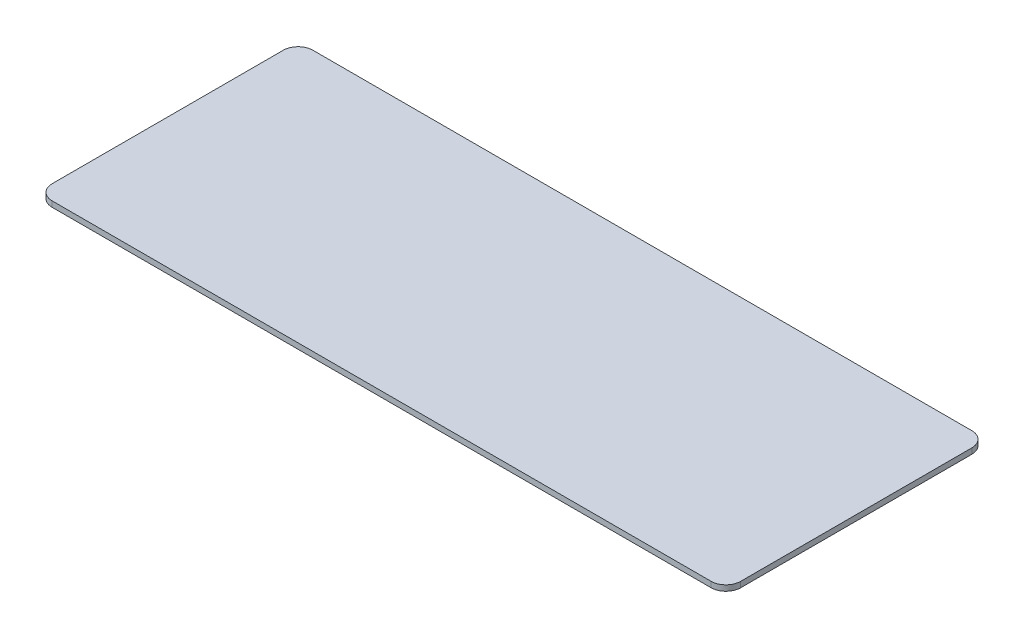
SolidWorks part; units mm, degrees
ref_plane "Front Plane" through (0, 0, 0) normal (0, 0, 1) x (1, 0, 0)
ref_plane "Top Plane" through (0, 0, 0) normal (0, 1, 0) x (1, 0, 0)
ref_plane "Right Plane" through (0, 0, 0) normal (1, 0, 0) x (0, 0, -1)
sketch "Sketch1" plane through (0, 0, 0) normal (0, 1, 0) x (1, 0, 0)
  line L1 (-184.1355, -69.7451) -> (184.1355, -69.7451)
  line L2 (-184.1355, -69.7451) -> (-184.1355, 69.7451)
  line L3 (-184.1355, 69.7451) -> (184.1355, 69.7451)
  line L4 (184.1355, -69.7451) -> (184.1355, 69.7451)
  line L5 (-184.1355, -69.7451) -> (184.1355, 69.7451) construction
  line L6 (-184.1355, 69.7451) -> (184.1355, -69.7451) construction
  point P0 (0, 0)
  dimension "D1" = 368.271
  dimension "D2" = 139.4902
extrude "Boss-Extrude1" add sketch "Sketch1" along normal mid plane 3
fillet "Fillet1" radius 7.9375 4 edges at (184.1355, 0, 69.7451) (-184.1355, 0, -69.7451) (184.1355, 0, -69.7451) (-184.1355, 0, 69.7451)
